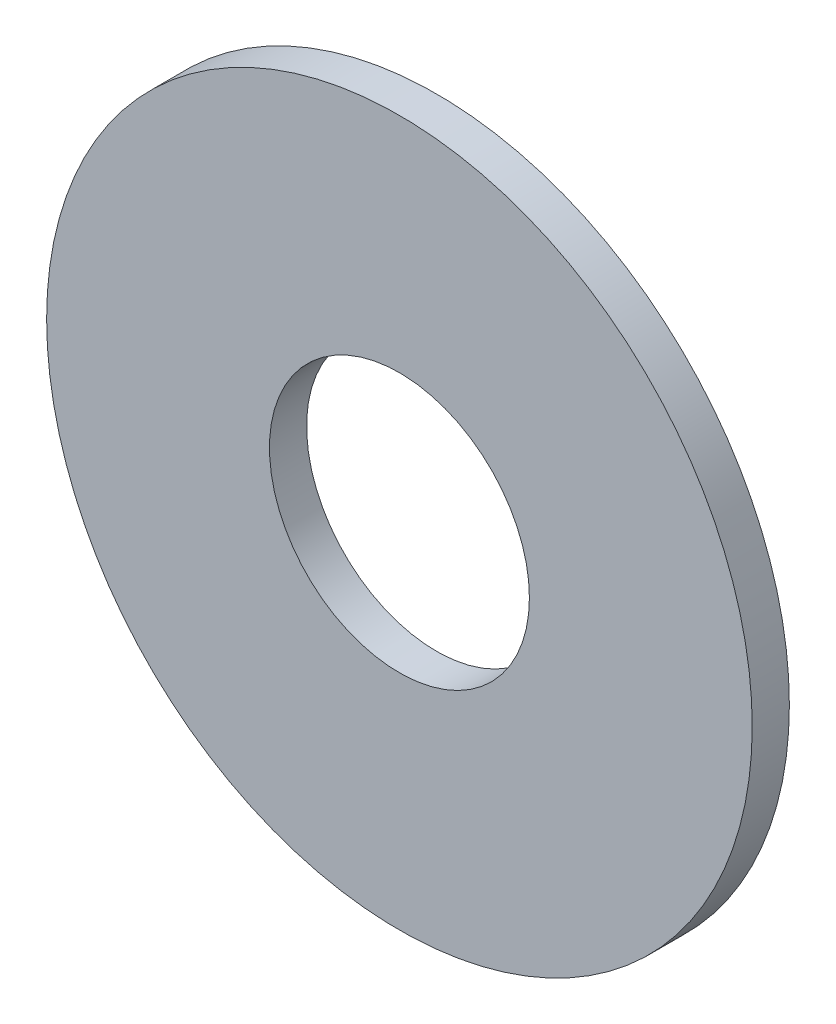
SolidWorks part; units mm, degrees
ref_plane "Front Plane" through (0, 0, 0) normal (0, 0, 1) x (1, 0, 0)
ref_plane "Top Plane" through (0, 0, 0) normal (0, 1, 0) x (1, 0, 0)
ref_plane "Right Plane" through (0, 0, 0) normal (1, 0, 0) x (0, 0, -1)
sketch "Sketch1" plane through (0, 0, 0) normal (0, 0, 1) x (1, 0, 0)
  circle A0 centre (0, 0) radius 1.75
  circle A1 centre (0, 0) radius 4.75
  dimension "D1" = 3.5
  dimension "D2" = 3
extrude "Boss-Extrude1" add sketch "Sketch1" along normal blind 0.5
